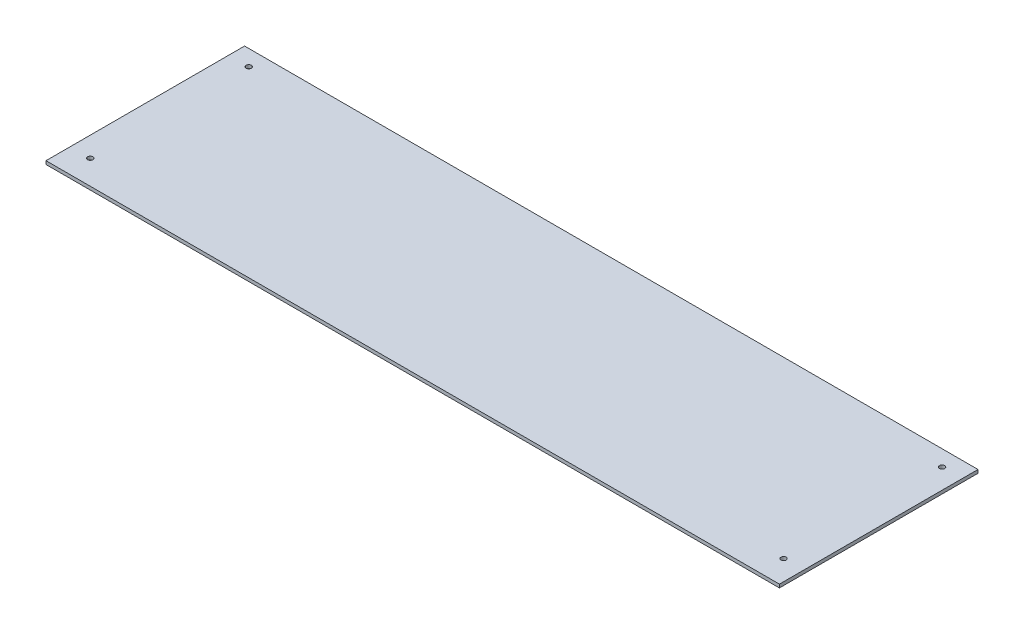
SolidWorks part; units mm, degrees
ref_plane "Alzado" through (0, 0, 0) normal (0, 0, 1) x (1, 0, 0)
ref_plane "Planta" through (0, 0, 0) normal (0, 1, 0) x (1, 0, 0)
ref_plane "Vista lateral" through (0, 0, 0) normal (1, 0, 0) x (0, 0, -1)
sketch "Croquis1" plane through (0, 0, 0) normal (0, 1, 0) x (1, 0, 0)
  line L0 (220.25, 120) -> (220.25, 0) construction
  line L1 (0, 0) -> (440.5, 0)
  line L2 (0, 0) -> (0, 120)
  line L3 (0, 120) -> (440.5, 120)
  line L4 (440.5, 0) -> (440.5, 120)
  line L5 (0, 60) -> (440.5, 60) construction
  circle A0 centre (12.5, 15) radius 1.55
  circle A1 centre (12.5, 110) radius 1.55
  circle A2 centre (428, 15) radius 1.55
  circle A3 centre (428, 110) radius 1.55
  dimension "D3" = 3.1
  dimension "D1" = 120
  dimension "D2" = 440.5
  dimension "D4" = 15
  dimension "D5" = 12.5
  dimension "D6" = 12.5
  dimension "D7" = 10
extrude "Saliente-Extruir1" add sketch "Croquis1" along normal blind 2
sketch "Croquis2" plane through (0, 0, 0) normal (0, -1, 0) x (1, 0, 0)
  line L0 (440, -0.5) -> (0.5, -0.5)
  line L1 (0.5, -0.5) -> (0.5, -119.5)
  line L2 (0.5, -119.5) -> (440, -119.5)
  line L3 (440, -119.5) -> (440, -0.5)
  line L4 (0, 0) -> (0, -120)
  line L5 (0, -120) -> (440.5, -120)
  line L6 (440.5, -120) -> (440.5, 0)
  line L7 (440.5, 0) -> (0, 0)
  line L8 (0, 0) -> (0, -120)
  line L9 (0, -120) -> (440.5, -120)
  line L10 (440.5, -120) -> (440.5, 0)
  line L11 (440.5, 0) -> (0, 0)
  dimension "D1" = 0
  dimension "D2" = 0.5
extrude "Cortar-Extruir1" cut sketch "Croquis2" against normal up to surface (2 mm away) up to face at (220.25, 2, -60)
